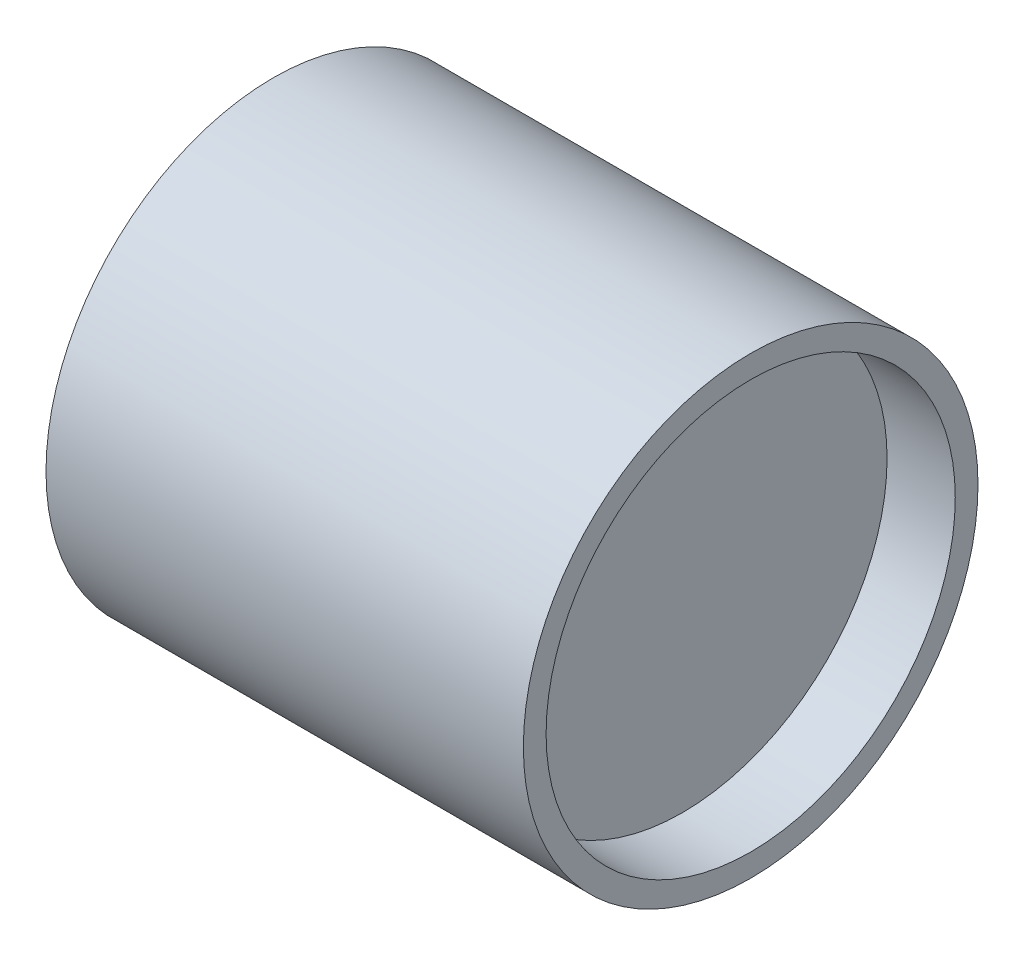
SolidWorks part; units mm, degrees
ref_plane "Plan1" through (0, 0, 0) normal (0, 0, 1) x (1, 0, 0)
ref_plane "Plan2" through (0, 0, 0) normal (0, 1, 0) x (1, 0, 0)
ref_plane "Plan3" through (0, 0, 0) normal (1, 0, 0) x (0, 0, -1)
sketch "Esquisse1" plane through (0, 0, 0) normal (0, 0, 1) x (1, 0, 0)
  line L0 (-13, 9) -> (-13, -9) construction
  line L1 (-13, 9) -> (-13, 0)
  line L2 (-28, -9) -> (-28, 9) construction
  line L3 (-28, 0) -> (-28, 9)
  line L5 (-10, 9) -> (-13, 9) construction
  line L6 (-30, 0) -> (-10, 0) construction
  line L7 (-10, 9) -> (-13, 9)
  line L8 (-28, 9) -> (-31, 9)
  line L9 (-31, 9) -> (-31, -9) construction
  line L11 (-31, 9) -> (-31, 10)
  line L12 (-31, 10) -> (-10, 10)
  line L13 (-10, 10) -> (-10, 9)
  line L14 (-28, 0) -> (-13, 0)
  line L15 (-41, 0) -> (-25.3834, 0) construction
  line L16 (0, 0) -> (-15.6166, 0) construction
  dimension "D1" = 10
revolve "Base-Révolution" add sketch "Esquisse1" angle 360 about L6
